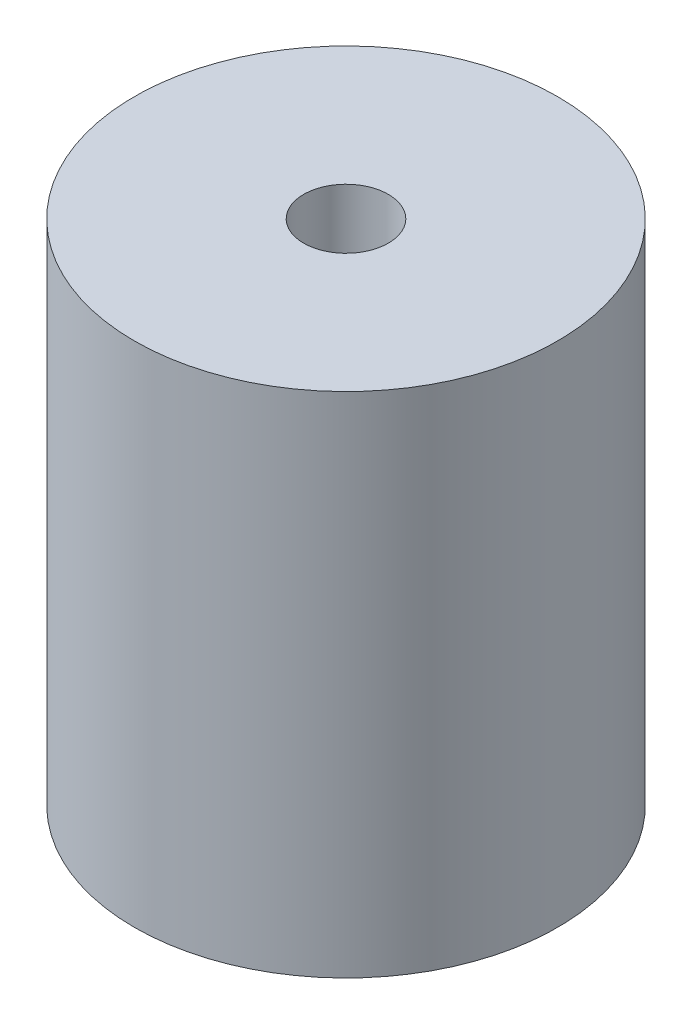
SolidWorks part; units mm, degrees
ref_plane "Front Plane" through (0, 0, 0) normal (0, 0, 1) x (1, 0, 0)
ref_plane "Top Plane" through (0, 0, 0) normal (0, 1, 0) x (1, 0, 0)
ref_plane "Right Plane" through (0, 0, 0) normal (1, 0, 0) x (0, 0, -1)
sketch "Sketch2" plane through (0, 0, 0) normal (0, 1, 0) x (1, 0, 0)
  circle A0 centre (0, 0) radius 12.5
  dimension "D1" = 25
extrude "Boss-Extrude1" add sketch "Sketch2" along normal mid plane 30
sketch "Sketch3" plane through (0, 15, 0) normal (0, 1, 0) x (1, 0, 0)
  circle A0 centre (0, 0) radius 2.5
  dimension "D1" = 5
extrude "Cut-Extrude1" cut sketch "Sketch3" against normal blind 15
sketch "Sketch4" plane through (0, -15, 0) normal (0, -1, 0) x (1, 0, 0)
  circle A0 centre (0, 0) radius 5
  dimension "D1" = 10
extrude "Cut-Extrude2" cut sketch "Sketch4" against normal blind 15
